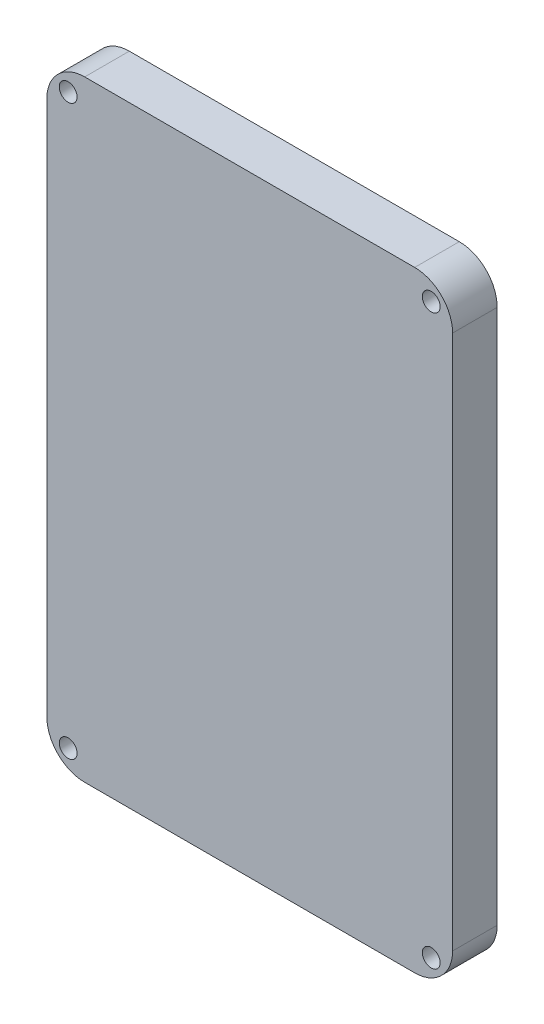
SolidWorks part; units mm, degrees
ref_plane "Front Plane" through (0, 0, 0) normal (1, 0, 0) x (0, 1, 0)
ref_plane "Top Plane" through (0, 0, 0) normal (0, 0, 1) x (0, 1, 0)
ref_plane "Right Plane" through (0, 0, 0) normal (0, 1, 0) x (-1, 0, 0)
sketch "Sketch1" plane through (0, 0, 0) normal (0, 0, 1) x (0, 1, 0)
  line L1 (-60, -45.5) -> (60, -45.5)
  line L2 (-68.5, -37) -> (-68.5, 37)
  line L3 (-60, 45.5) -> (60, 45.5)
  line L4 (68.5, -37) -> (68.5, 37)
  line L5 (-68.5, -45.5) -> (68.5, 45.5) construction
  line L6 (-68.5, 45.5) -> (68.5, -45.5) construction
  arc A0 (60, -45.5) -> (68.5, -37) centre (60, -37) ccw
  arc A1 (-60, -45.5) -> (-68.5, -37) centre (-60, -37) cw
  arc A2 (-68.5, 37) -> (-60, 45.5) centre (-60, 37) cw
  arc A3 (60, 45.5) -> (68.5, 37) centre (60, 37) cw
  point P0 (0, 0)
  dimension "D3" = 8.5
  dimension "D1" = 91
  dimension "D2" = 137
extrude "Case" add sketch "Sketch1" along normal blind 10
sketch "Sketch2" plane through (0, 0, 10) normal (0, 0, 1) x (1, 0, 0)
  line L1 (-37, -62) -> (37, -62)
  line L2 (-39, -60) -> (-39, 60)
  line L3 (-37, 62) -> (37, 62)
  line L4 (39, -60) -> (39, 60)
  line L5 (-39, -62) -> (39, 62) construction
  line L6 (-39, 62) -> (39, -62) construction
  arc A0 (37, -62) -> (39, -60) centre (37, -60) ccw
  arc A1 (-37, -62) -> (-39, -60) centre (-37, -60) cw
  arc A2 (37, 62) -> (39, 60) centre (37, 60) cw
  arc A3 (-39, 60) -> (-37, 62) centre (-37, 60) cw
  point P0 (0, 0)
  dimension "D3" = 2
  dimension "D1" = 124
  dimension "D2" = 78
extrude "internal slot" cut sketch "Sketch2" along direction (0, 0, 1) on the side against the normal blind 3 from offset 2 contours L2 A3 L3 A2 L4 A0 L1 A1 offset against normal yes
sketch "Sketch3" plane through (0, 0, 10) normal (0, 0, 1) x (1, 0, 0)
  line L0 (0, 68.5) -> (0, -68.5) construction
  line L1 (37, 68.5) -> (-37, 68.5) construction
  line L2 (-37, -68.5) -> (37, -68.5) construction
  line L3 (-45.5, 0) -> (45.5, 0) construction
  line L4 (-45.5, 60) -> (-45.5, -60) construction
  line L5 (45.5, -60) -> (45.5, 60) construction
  line L6 (-43.0104, 66.0104) -> (-38.4142, 61.4142) construction
  circle A2 centre (-40.7123, 63.7123) radius 2
  circle A3 centre (-40.7123, -63.7123) radius 2
  circle A4 centre (40.7123, 63.7123) radius 2
  circle A5 centre (40.7123, -63.7123) radius 2
  arc A6 (-37, 68.5) -> (-45.5, 60) centre (-37, 60) ccw construction
  point P18 (-40.1276, 61.7997)
  point P26 (0, 0)
  point P27 (-40.7123, 63.7123)
  dimension "D1" = 6.5
  dimension "D2" = 4
extrude "Cut-Extrude1" cut sketch "Sketch3" against normal through all both and the other way through all
